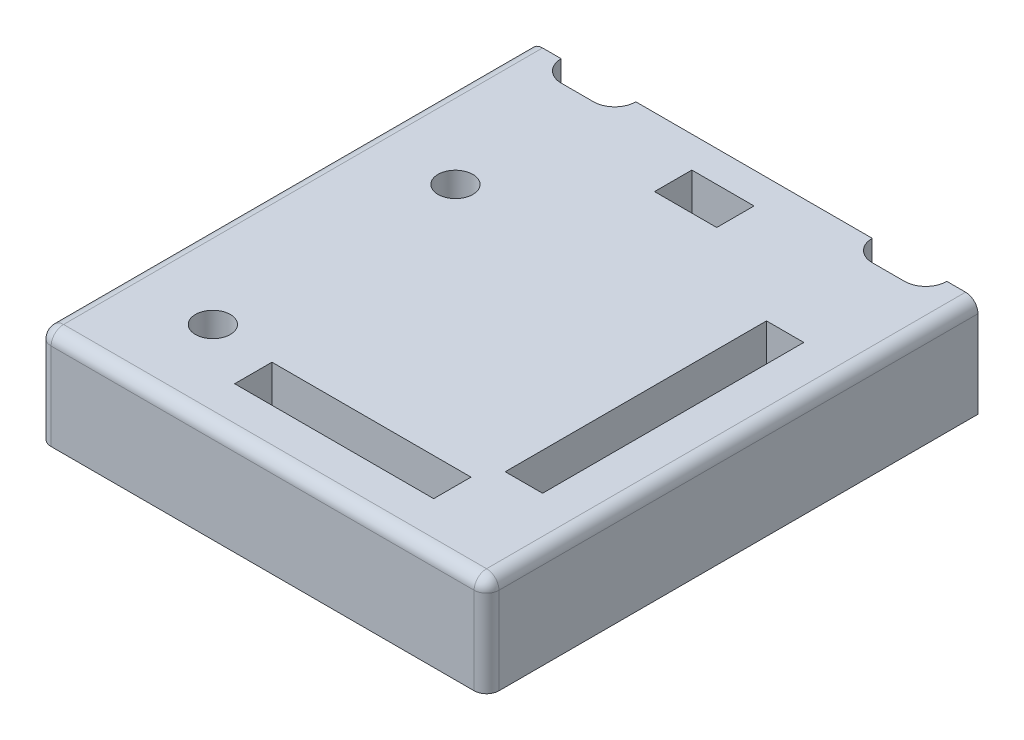
SolidWorks part; units mm, degrees
ref_plane "Front Plane" through (0, 0, 0) normal (0, 0, 1) x (1, 0, 0)
ref_plane "Top Plane" through (0, 0, 0) normal (0, 1, 0) x (1, 0, 0)
ref_plane "Right Plane" through (0, 0, 0) normal (1, 0, 0) x (0, 0, -1)
sketch "Sketch1" plane through (0, 0, 0) normal (0, 1, 0) x (1, 0, 0)
  line L1 (-18, 16.75) -> (18, 16.75)
  line L2 (-18, 16.75) -> (-18, -16.75)
  line L3 (-18, -16.75) -> (18, -16.75)
  line L4 (18, 16.75) -> (18, -16.75)
  line L5 (11, 12.75) -> (14, 12.75)
  line L6 (11, 12.75) -> (11, -8.25)
  line L7 (11, -8.25) -> (14, -8.25)
  line L8 (14, 12.75) -> (14, -8.25)
  line L9 (10, -10) -> (-6, -10)
  line L10 (10, -10) -> (10, -13)
  line L11 (10, -13) -> (-6, -13)
  line L12 (-6, -10) -> (-6, -13)
  circle A0 centre (-11, -9.75) radius 1.4
  circle A1 centre (-11, 9.75) radius 1.4
  point P4 (0, 16.75)
  point P6 (18, 0)
  dimension "D3" = 2.8
  dimension "D1" = 36
  dimension "D2" = 33.5
  dimension "D4" = 7
  dimension "D5" = 7
  dimension "D6" = 7
  dimension "D7" = 7
  dimension "D8" = 3
  dimension "D9" = 4
  dimension "D10" = 4
  dimension "D11" = 21
  dimension "D12" = 3.75
  dimension "D13" = 3
  dimension "D14" = 16
  dimension "D15" = 8
extrude "Base" add sketch "Sketch1" along normal blind 8
sketch "Sketch3" plane through (0, 0, 0) normal (0, -1, 0) x (1, 0, 0)
  line L1 (-15.5, 14.25) -> (15.5, 14.25)
  line L2 (-15.5, 14.25) -> (-15.5, -14.25)
  line L3 (-15.5, -14.25) -> (15.5, -14.25)
  line L4 (15.5, 14.25) -> (15.5, -14.25)
  point P4 (-15.5, 0)
  point P6 (0, 14.25)
  dimension "D1" = 28.5
  dimension "D2" = 31
extrude "Interior Cutout" cut sketch "Sketch3" against normal blind 5
sketch "Sketch5" plane through (0, 0, 0) normal (0, 1, 0) x (1, 0, 0)
  line L0 (-18, 16.75) -> (18, 16.75)
  line L3 (-18, 16.75) -> (-18, 22.75)
  line L4 (18, 16.75) -> (18, 22.75)
  line L5 (-18, 22.75) -> (-15.5, 22.75)
  line L6 (-9.5, 22.75) -> (9.5, 22.75)
  line L7 (15.5, 22.75) -> (18, 22.75)
  line L8 (-13.8, 21.05) -> (-11.2, 21.05)
  line L9 (11.2, 21.05) -> (13.8, 21.05)
  arc A0 (-13.8, 21.05) -> (-15.5, 22.75) centre (-13.8, 22.75) cw
  arc A1 (-11.2, 21.05) -> (-9.5, 22.75) centre (-11.2, 22.75) ccw
  arc A2 (11.2, 21.05) -> (9.5, 22.75) centre (11.2, 22.75) cw
  arc A3 (13.8, 21.05) -> (15.5, 22.75) centre (13.8, 22.75) ccw
  point P19 (-12.5, 21.05)
  point P20 (12.5, 21.05)
  dimension "D3" = 1.7
  dimension "D1" = 6
  dimension "D2" = 6
  dimension "D4" = 6
  dimension "D5" = 2.6
  dimension "D6" = 25
  dimension "D7" = 2.5
extrude "Basket Mounting Edge" add sketch "Sketch5" along normal up to surface (8 mm away) up to face at (-11, 8, 11.15)
sketch "Sketch6" plane through (0, 0, -22.75) normal (0, 0, -1) x (-1, 0, 0)
  line L0 (-9.5, 4) -> (9.5, 4) construction
  line L1 (-9.5, 8) -> (-9.5, 0) construction
  line L2 (9.5, 8) -> (9.5, 0) construction
  line L3 (0, 8) -> (0, 0) construction
  line L4 (-9.5, 8) -> (9.5, 8) construction
  line L5 (-9.5, 0) -> (9.5, 0) construction
  circle A0 centre (-5, 4) radius 1.4
  circle A1 centre (5, 4) radius 1.4
  dimension "D1" = 2.8
  dimension "D2" = 4.5
extrude "Basket Mounting Screw Holes" cut sketch "Sketch6" against normal blind 7
sketch "Sketch7" plane through (0, 8, 0) normal (0, 1, 0) x (1, 0, 0)
  line L0 (9.5, 22.75) -> (-9.5, 22.75) construction
  line L1 (-2.5, 20.25) -> (2.5, 20.25)
  line L2 (-2.5, 20.25) -> (-2.5, 17.25)
  line L3 (-2.5, 17.25) -> (2.5, 17.25)
  line L4 (2.5, 20.25) -> (2.5, 17.25)
  point P6 (0, 22.75)
  point P7 (0, 20.25)
  dimension "D1" = 2.5
  dimension "D2" = 5
  dimension "D3" = 3
extrude "Zip Tie Hole" cut sketch "Sketch7" against normal through all
fillet "1mm Edge Fillets" radius 1 5 edges at (-18, 4, 16.75) (-18, 8, -3) (0, 8, 16.75) (18, 8, -3) (18, 4, 16.75)
equation "\"D4@Sketch1\"=\"D7@Sketch1\""
equation "\"D5@Sketch1\"=\"D7@Sketch1\""
equation "\"D6@Sketch1\"=\"D7@Sketch1\""
